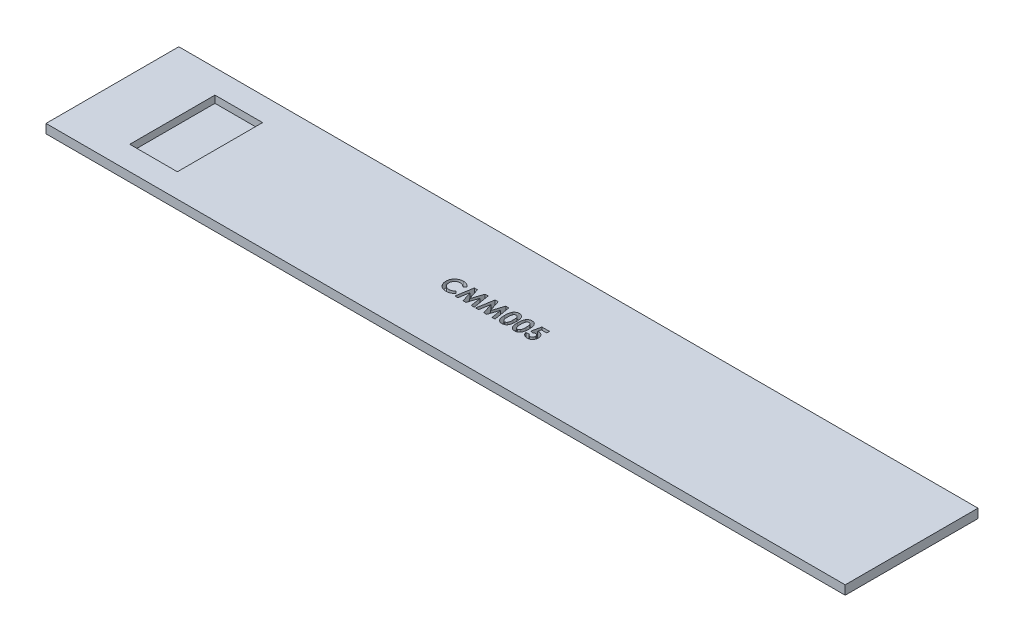
SolidWorks part; units mm, degrees
ref_plane "Front Plane" through (0, 0, 0) normal (0, 0, 1) x (1, 0, 0)
ref_plane "Top Plane" through (0, 0, 0) normal (0, 1, 0) x (1, 0, 0)
ref_plane "Right Plane" through (0, 0, 0) normal (1, 0, 0) x (0, 0, -1)
sketch "Sketch1" plane through (0, 0, 0) normal (0, 1, 0) x (1, 0, 0)
  line L1 (0, 0) -> (167.9, 0)
  line L2 (0, 0) -> (0, 27.9)
  line L3 (0, 27.9) -> (167.9, 27.9)
  line L4 (167.9, 0) -> (167.9, 27.9)
  dimension "D1" = 167.9
  dimension "D2" = 27.9
extrude "Boss-Extrude1" add sketch "Sketch1" along normal blind 1.9
sketch "Sketch2" plane through (0, 1.9, 0) normal (0, 1, 0) x (1, 0, 0)
  line L0 (167.9, 27.9) -> (0, 27.9) construction
  line L1 (12.5979, 22.9) -> (22.5979, 22.9)
  line L2 (12.5979, 22.9) -> (12.5979, 5)
  line L3 (12.5979, 5) -> (22.5979, 5)
  line L4 (22.5979, 22.9) -> (22.5979, 5)
  line L5 (0, 0) -> (167.9, 0) construction
  dimension "D1" = 5
  dimension "D2" = 5
  dimension "D3" = 10
extrude "Cut-Extrude1" cut sketch "Sketch2" against normal blind 1.5
sketch "Sketch4" plane through (0, 1.9, 0) normal (0, 1, 0) x (1, 0, 0)
  text T0 "<b>CMM005</b>" font "Century Gothic" height 3.5
  point P1 (70.4851, 11.552)
extrude "Cut-Extrude2" cut sketch "Sketch4" against normal blind 1.25
